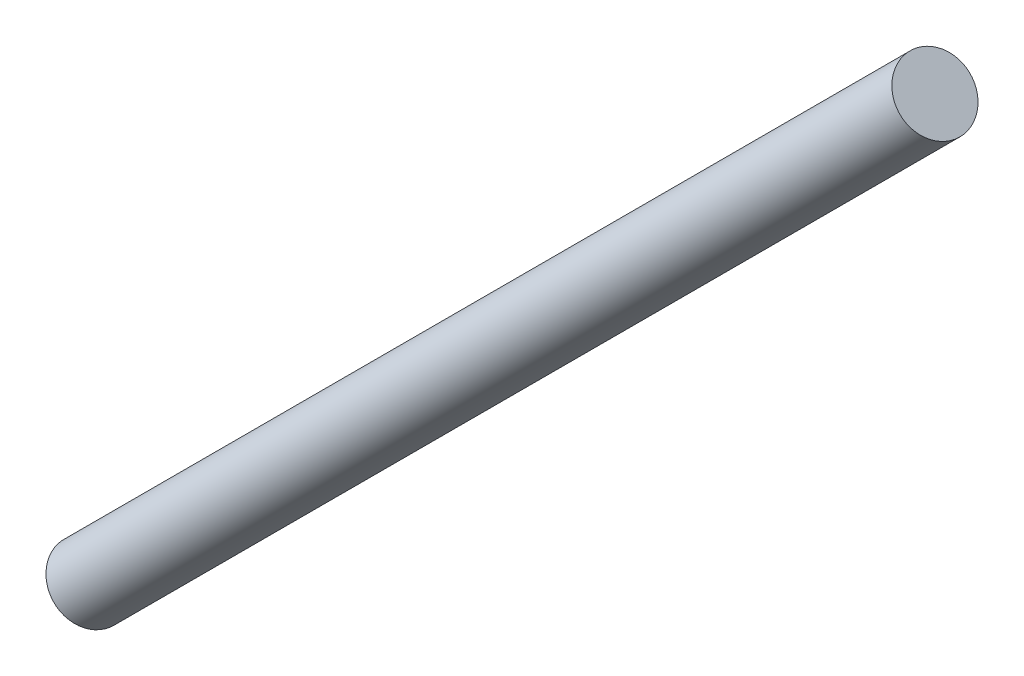
SolidWorks part; units mm, degrees
ref_plane "Front Plane" through (0, 0, 0) normal (0, 0, 1) x (1, 0, 0)
ref_plane "Top Plane" through (0, 0, 0) normal (0, 1, 0) x (1, 0, 0)
ref_plane "Right Plane" through (0, 0, 0) normal (1, 0, 0) x (0, 0, -1)
sketch "Sketch2" plane through (94.8593, 94.8593, 0) normal (-0.7071, -0.7071, 0) x (0, 0, 1)
  circle A1 centre (-10, -38.4567) radius 5
  circle A2 centre (-10, -38.4567) radius 5
  dimension "D1" = 0
extrude "Boss-Extrude1" add sketch "Sketch2" along normal blind 170
